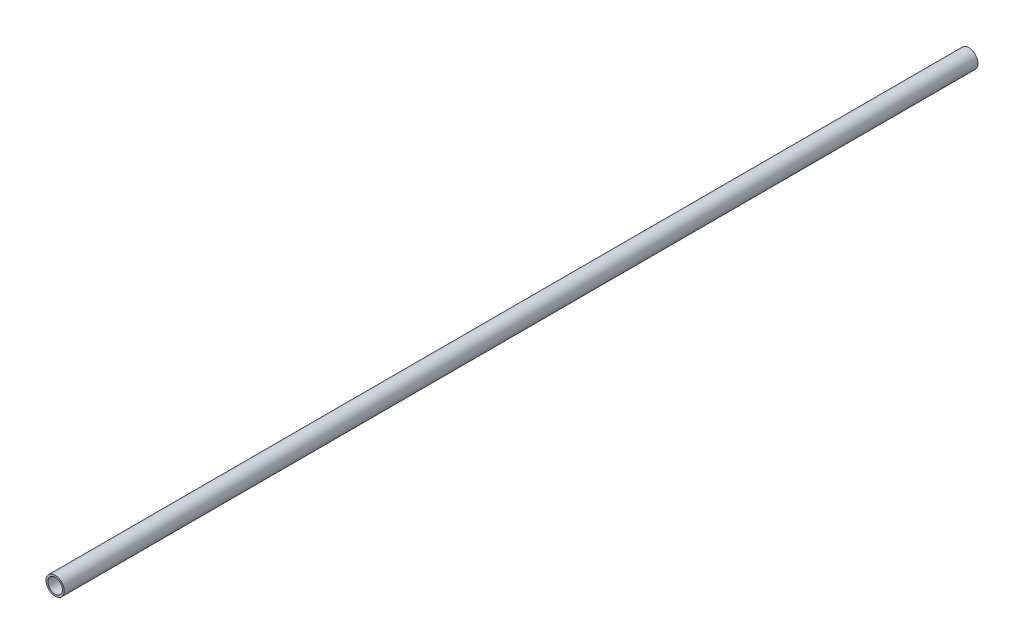
SolidWorks part; units mm, degrees
ref_plane "前基準面" through (0, 0, 0) normal (0, 0, 1) x (1, 0, 0)
ref_plane "上基準面" through (0, 0, 0) normal (0, 1, 0) x (1, 0, 0)
ref_plane "右基準面" through (0, 0, 0) normal (1, 0, 0) x (0, 0, -1)
sketch "草圖1" plane through (0, 0, 0) normal (0, 0, 1) x (1, 0, 0)
  circle A0 centre (0, 0) radius 25
  circle A1 centre (0, 0) radius 20
  dimension "D1" = 40
  dimension "D2" = 50
extrude "填料-伸長1" add sketch "草圖1" along normal blind 2500
